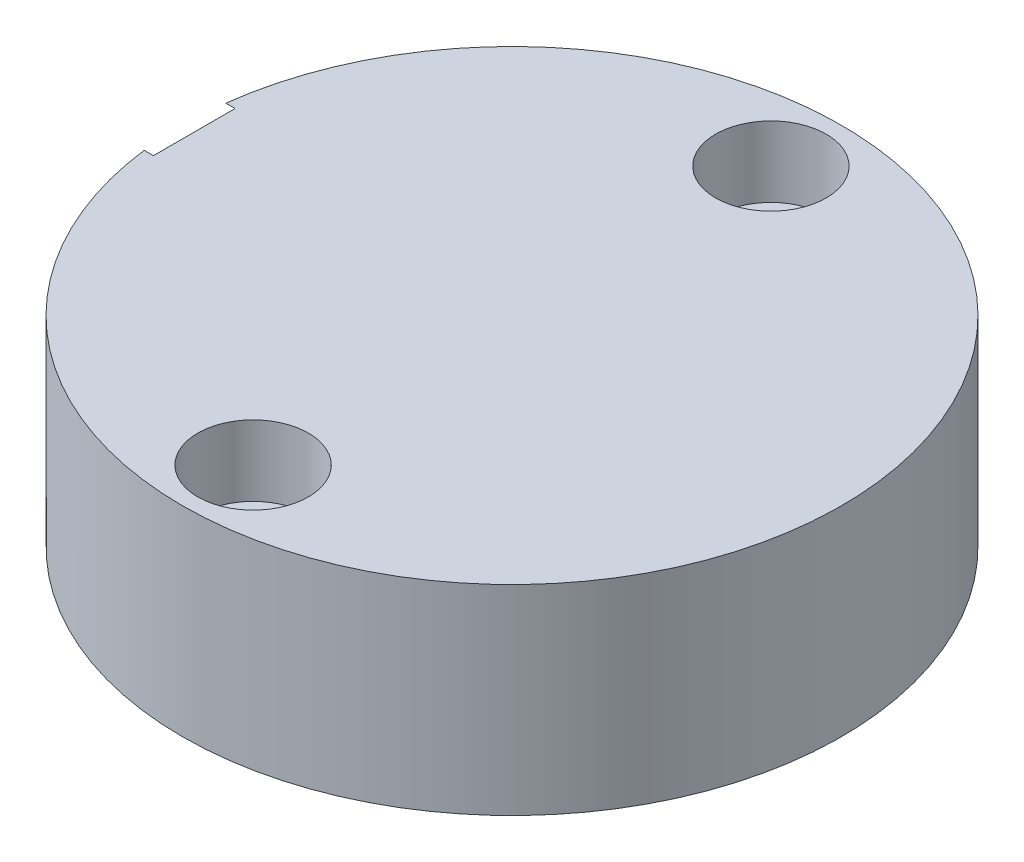
SolidWorks part; units mm, degrees
material "6061-T6 (SS)"
ref_plane "Front Plane" through (0, 0, 0) normal (0, 0, 1) x (1, 0, 0)
ref_plane "Top Plane" through (0, 0, 0) normal (0, 1, 0) x (1, 0, 0)
ref_plane "Right Plane" through (0, 0, 0) normal (1, 0, 0) x (0, 0, -1)
ref_plane "Plane1" through (0, 0, 0) normal (0, 0, -1) x (-1, 0, 0)
sketch "Sketch1" plane through (0, 0, 0) normal (0, 0, -1) x (-1, 0, 0)
  line L0 (-14.224, 0) -> (0, 0)
  line L1 (0, 0) -> (0, 8.636)
  line L2 (0, 8.636) -> (-14.224, 8.636)
  line L3 (-14.224, 8.636) -> (-14.224, 0)
  line L4 (0, 0) -> (0, 8.636) construction
revolve "Revolve1" add sketch "Sketch1" angle 360 about L4
hole_wizard "CBORE for M2.5 Hex Head Machine Screw1" positions "Sketch3" profile "Sketch2" counterbore size "M2.5" standard "ANSI Metric"
sketch "Sketch3" plane through (0, 8.636, 0) normal (0, 1, 0) x (1, 0, 0)
  point P0 (0, -11.176)
  point P1 (0, 11.176)
sketch "Sketch2" plane through (0, 8.636, 11.176) normal (1, 0, 0) x (0, 0, 1)
  line L0 (0, 0) -> (0, 8.636)
  line L1 (0, 8.636) -> (1.524, 8.636)
  line L3 (1.524, 8.636) -> (1.524, 3.048)
  line L4 (1.524, 3.048) -> (2.3876, 3.048)
  line L5 (2.3876, 3.048) -> (2.3876, 0)
  line L7 (2.3876, 0) -> (0, 0)
  line L11 (0, -6.35) -> (0, 107.95) construction
  dimension "Thru Hole Dia." = 3.048
  dimension "Thru Hole Depth" = 8.636
  dimension "C'Bore Dia." = 4.7752
  dimension "C'Bore Depth" = 3.048
hole_wizard "M2.5 Clearance Hole1" positions "Sketch5" profile "Sketch4" hole size "M2.5" standard "ANSI Metric"
sketch "Sketch5" plane through (0, 0, 0) normal (0, -1, 0) x (-1, 0, 0)
  point P0 (-7.9026, 7.9026)
  point P1 (7.9026, -7.9026)
  point P2 (-7.9026, -7.9026)
  point P3 (7.9026, 7.9026)
sketch "Sketch4" plane through (7.9026, 0, -7.9026) normal (1, 0, 0) x (0, 0, -1)
  line L0 (0, 0) -> (0, 2.54)
  line L1 (0, 2.54) -> (1.524, 2.54)
  line L2 (1.524, 2.54) -> (1.524, 0)
  line L5 (1.524, 0) -> (0, 0)
  line L10 (0, 2.54) -> (-1.524, 2.54) construction
  line L11 (0, -6.35) -> (0, 107.95) construction
  dimension "Hole Dia." = 3.048
  dimension "Hole Depth" = 2.54
  dimension "Drill Angle" = 180
hole_wizard "M13 Clearance Hole1" positions "Sketch7" profile "Sketch6" hole size "M13" standard "ANSI Metric"
sketch "Sketch7" plane through (0, 0, 0) normal (0, -1, 0) x (-1, 0, 0)
  point P0 (0, 0)
sketch "Sketch6" plane through (0, 0, 0) normal (1, 0, 0) x (0, 0, -1)
  line L0 (0, 0) -> (0, 2.54)
  line L1 (0, 2.54) -> (7.747, 2.54)
  line L2 (7.747, 2.54) -> (7.747, 0)
  line L5 (7.747, 0) -> (0, 0)
  line L10 (0, 2.54) -> (-7.747, 2.54) construction
  line L11 (0, -6.35) -> (0, 107.95) construction
  dimension "Hole Dia." = 15.494
  dimension "Hole Depth" = 2.54
  dimension "Drill Angle" = 180
hole_wizard "CBORE for M3.5 Hex Head Machine Screw1" positions "3DSketch1" profile "Sketch8" counterbore size "M3.5" standard "ANSI Metric"
sketch3d "3DSketch1"
  point P0 (-14.224, 5.08, 0)
sketch "Sketch8" plane through (-14.224, 5.08, 0) normal (0, 1, 0) x (0, 0, 1)
  line L0 (0, 0) -> (0, 8.2573)
  line L1 (0, 8.2573) -> (1.9837, 7.112)
  line L2 (1.9837, 7.112) -> (1.9837, 0.508)
  line L3 (1.9837, 0.508) -> (3.9687, 0.508)
  line L4 (3.9687, 0.508) -> (3.9687, 0)
  line L5 (3.9687, 0) -> (0, 0)
  line L10 (0, 8.2573) -> (-1.9837, 7.112) construction
  line L11 (0, -6.35) -> (0, 107.95) construction
  dimension "Hole Dia." = 3.9675
  dimension "Hole Depth" = 7.112
  dimension "C'Bore Dia." = 7.9375
  dimension "C'Bore Depth" = 0.508
  dimension "Drill Angle" = 120
chamfer "Chamfer1" distance 0.4293 angle 45 1 edges at (-13.716, 5.08, 1.9837)
